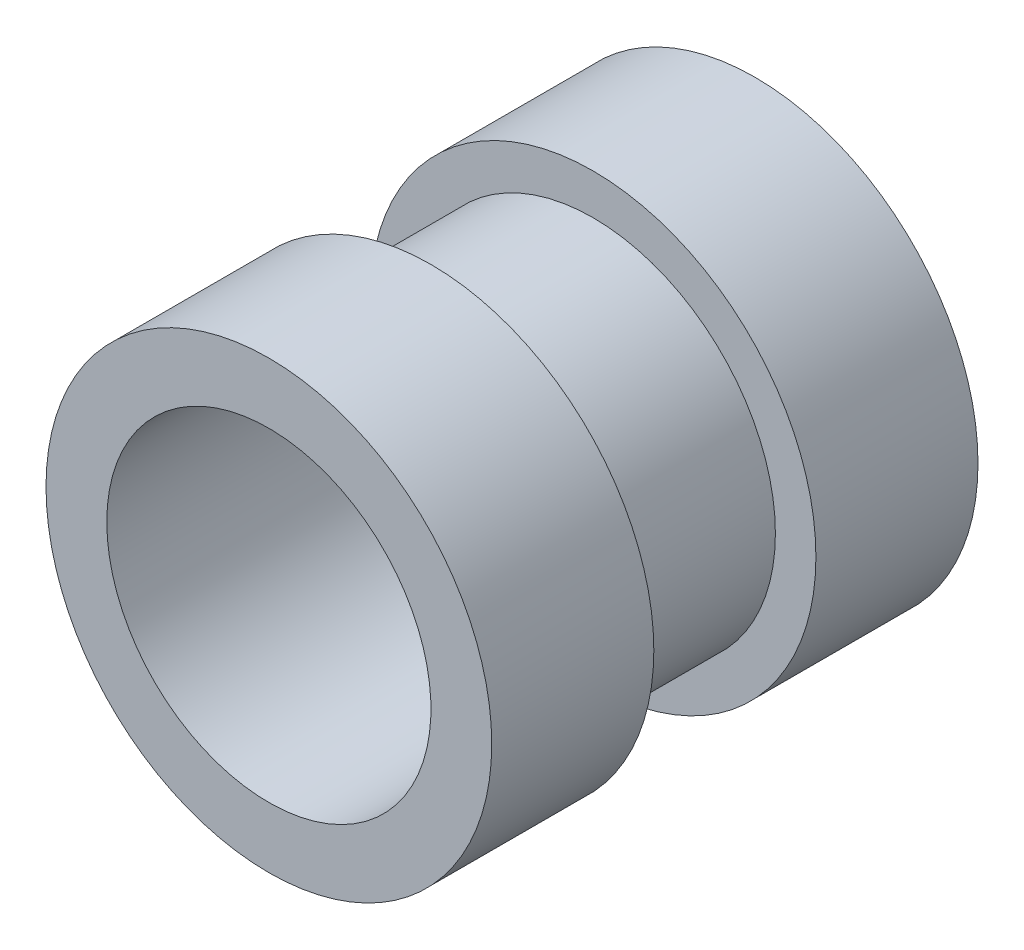
SolidWorks part; units mm, degrees
ref_plane "Front Plane" through (0, 0, 0) normal (0, 0, 1) x (1, 0, 0)
ref_plane "Top Plane" through (0, 0, 0) normal (0, 1, 0) x (1, 0, 0)
ref_plane "Right Plane" through (0, 0, 0) normal (1, 0, 0) x (0, 0, -1)
sketch "Sketch1" plane through (0, 0, 0) normal (0, 1, 0) x (1, 0, 0)
  line L0 (0, 0) -> (2.75, 0)
  line L1 (2.75, 0) -> (2.75, 2)
  line L2 (2.75, 2) -> (2.25, 2)
  line L3 (2.25, 2) -> (2.25, 4)
  line L4 (2.25, 4) -> (2.75, 4)
  line L5 (2.75, 4) -> (2.75, 6)
  line L6 (2.75, 6) -> (0, 6)
  line L7 (0, 6) -> (0, 0)
  line L8 (0, 11.944) -> (0, -8.2859) construction
  dimension "D1" = 6
  dimension "D2" = 2
  dimension "D3" = 2
  dimension "D4" = 0.5
  dimension "D5" = 2.75
revolve "Revolve1" add sketch "Sketch1" angle 360 about L8
sketch "Sketch2" plane through (0, 0, -6) normal (0, 0, -1) x (-1, 0, 0)
  circle A0 centre (0, 0) radius 2
  dimension "D1" = 4
extrude "Cut-Extrude1" cut sketch "Sketch2" against normal through all
